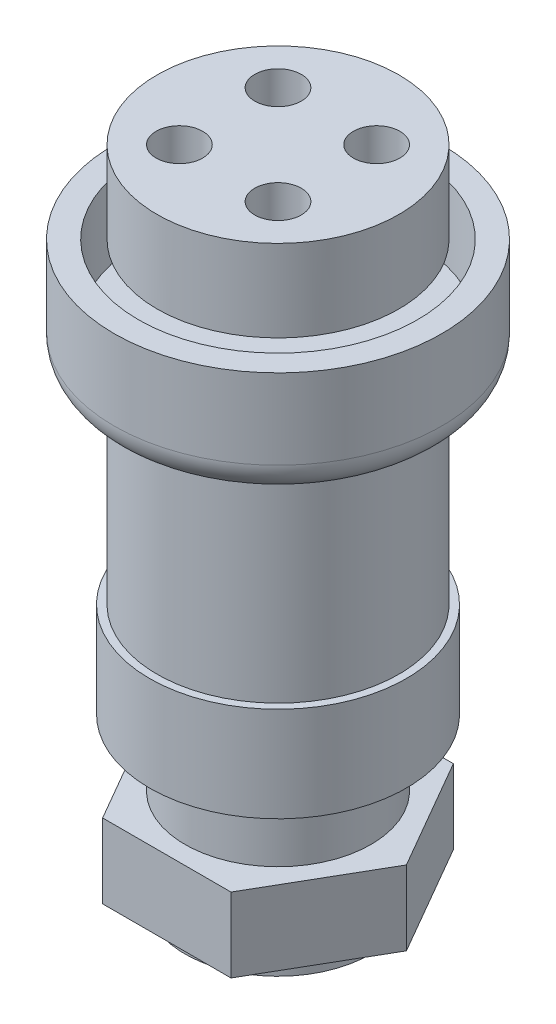
SolidWorks part; units mm, degrees
ref_plane "Płaszczyzna przednia" through (0, 0, 0) normal (0, 0, 1) x (1, 0, 0)
ref_plane "Płaszczyzna górna" through (0, 0, 0) normal (0, 1, 0) x (1, 0, 0)
ref_plane "Płaszczyzna prawa" through (0, 0, 0) normal (1, 0, 0) x (0, 0, -1)
sketch "Szkic17" plane through (0, 0, 0) normal (0, 0, 1) x (1, 0, 0)
  line L1 (14.2492, 9.3) -> (20.7492, 9.3) construction
  line L2 (20.7492, 9.3) -> (20.7492, 0) construction
  line L3 (20.7492, 0) -> (21.4992, 0) construction
  line L4 (21.4992, 0) -> (21.4992, -1.1) construction
  line L5 (21.4992, -1.1) -> (20.7492, -1.1) construction
  line L6 (21.4992, -1.1) -> (20.5992, -1.1) construction
  line L7 (20.7492, -1.1) -> (20.7492, -12.1) construction
  line L8 (20.5992, -12.1) -> (21.1492, -12.1) construction
  line L9 (20.7492, -12.1) -> (21.1492, -12.1) construction
  line L10 (21.1492, -12.1) -> (21.1492, -17.2) construction
  line L11 (21.1492, -17.2) -> (19.2492, -18.1786) construction
  line L12 (19.2492, -18.1786) -> (19.2492, -25.8737) construction
  line L13 (19.2492, -25.8737) -> (14.2492, -25.8737) construction
  line L14 (14.2492, -25.8737) -> (14.2492, 9.3) construction
sketch "Szkic18" plane through (0, 0, 0) normal (0, 0, 1) x (1, 0, 0)
  line L0 (14.2492, 9.3) -> (20.7492, 9.3)
  line L1 (20.7492, 9.3) -> (20.7492, 0)
  line L2 (20.7492, 0) -> (21.4992, 0)
  line L3 (21.4992, 0) -> (21.4992, -1.1)
  line L4 (21.4992, -1.1) -> (20.7492, -1.1)
  line L5 (20.7492, -1.1) -> (20.7492, -12.1)
  line L6 (20.7492, -12.1) -> (21.1492, -12.1)
  line L7 (21.1492, -12.1) -> (21.1492, -17.2)
  line L8 (21.1492, -17.2) -> (19.2492, -18.1786)
  line L9 (19.2492, -18.1786) -> (19.2492, -25.8737)
  line L10 (19.2492, -25.8737) -> (14.2492, -25.8737)
  line L11 (14.2492, -25.8737) -> (14.2492, 9.3)
revolve "Obrót4" add sketch "Szkic18" angle 360 about L11
sketch "Szkic19" plane through (0, 9.3, 0) normal (0, 1, 0) x (1, 0, 0)
  line L1 (11.5992, 2.65) -> (16.8992, 2.65) construction
  line L2 (11.5992, 2.65) -> (11.5992, -2.65) construction
  line L3 (11.5992, -2.65) -> (16.8992, -2.65) construction
  line L4 (16.8992, 2.65) -> (16.8992, -2.65) construction
  line L5 (11.5992, 2.65) -> (16.8992, -2.65) construction
  line L6 (11.5992, -2.65) -> (16.8992, 2.65) construction
  circle A0 centre (11.5992, 2.65) radius 1.25
  circle A1 centre (16.8992, 2.65) radius 1.25
  circle A2 centre (16.8992, -2.65) radius 1.25
  circle A3 centre (11.5992, -2.65) radius 1.25
  point P0 (14.2492, 0)
  dimension "D1" = 2
  dimension "D2" = 2
extrude "Wytnij-wyciągnięcie2" cut sketch "Szkic19" against normal blind 6
ref_plane "Płaszczyzna8" through (0, -24.7737, 0) normal (0, -1, 0) x (-1, 0, 0)
sketch "Szkic20" plane through (0, -24.7737, 0) normal (0, -1, 0) x (-1, 0, 0)
  line L1 (-7.3492, 0) -> (-10.7992, 5.9756)
  line L2 (-10.7992, 5.9756) -> (-17.6992, 5.9756)
  line L3 (-17.6992, 5.9756) -> (-21.1492, 0)
  line L4 (-21.1492, 0) -> (-17.6992, -5.9756)
  line L5 (-17.6992, -5.9756) -> (-10.7992, -5.9756)
  line L6 (-10.7992, -5.9756) -> (-7.3492, 0)
  circle A0 centre (-14.2492, 0) radius 5.9756 construction
extrude "Dodanie-wyciągnięcie1" add sketch "Szkic20" against normal blind 4
sketch "Szkic21" plane through (0, -1.1, 0) normal (0, -1, 0) x (1, 0, 0)
  circle A0 centre (14.2492, 0) radius 8.8
extrude "Dodanie-wyciągnięcie2" add sketch "Szkic21" against normal blind 6
fillet "Zaokrąglenie1" radius 1.7 1 edges at (14.2492, -1.1, -8.8)
sketch "Szkic22" plane through (0, 4.9, 0) normal (0, 1, 0) x (1, 0, 0)
  circle A0 centre (14.2492, 0) radius 7.5
extrude "Wytnij-wyciągnięcie3" cut sketch "Szkic22" against normal blind 4
